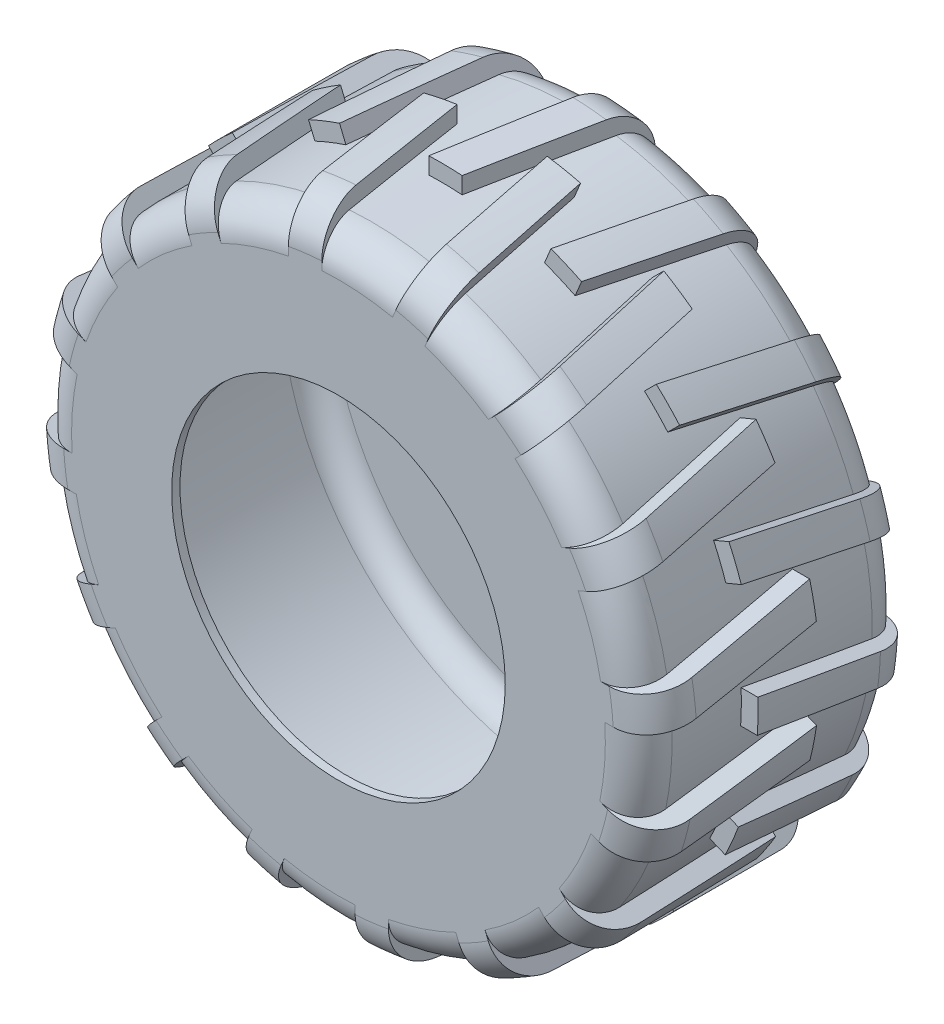
SolidWorks part; units mm, degrees
material "BUTYL"
ref_plane "Front Plane" through (0, 0, 0) normal (0, 0, 1) x (1, 0, 0)
ref_plane "Top Plane" through (0, 0, 0) normal (0, 1, 0) x (1, 0, 0)
ref_plane "Right Plane" through (0, 0, 0) normal (1, 0, 0) x (0, 0, -1)
sketch "Sketch1" plane through (0, 0, 0) normal (1, 0, 0) x (0, 0, -1)
  line L0 (0, 0) -> (-485.5709, 0) construction
  line L1 (-485.5709, 0) -> (498.8598, 0) construction
  line L2 (498.8598, 0) -> (0, 0) construction
  line L3 (0, 0) -> (0, -268.8161) construction
  line L4 (0, -268.8161) -> (0, 238.9616) construction
  line L5 (-203.2, 406.4) -> (-203.2, 254)
  line L6 (203.2, 406.4) -> (203.2, 254)
  line L7 (-152.4, 457.2) -> (152.4, 457.2)
  line L8 (0, 238.9616) -> (0, 521.9878) construction
  arc A0 (-152.4, 457.2) -> (-203.2, 406.4) centre (-152.4, 406.4) ccw
  arc A1 (203.2, 406.4) -> (152.4, 457.2) centre (152.4, 406.4) ccw
  point P8 (0, 457.2)
  point P11 (0, 457.2)
  point P13 (0, 0)
  dimension "D3" = 457.2
  dimension "D5" = 50.8
  dimension "D6" = 50.8
  dimension "D1" = 406.4
  dimension "D2" = 152.4
  dimension "D4" = 152.4
revolve "Revolve-Thin1" add sketch "Sketch1" angle 360 about L1 wall 12.7
ref_plane "Plane1" through (0, 482.6, 0) normal (0, 1, 0) x (1, 0, 0)
sketch "Sketch2" plane through (0, 482.6, 0) normal (0, 1, 0) x (1, 0, 0)
  line L0 (0, 0) -> (0, 264.3409) construction
  line L1 (0, 264.3409) -> (0, -257.8079) construction
  line L2 (0, -257.8079) -> (0, 0) construction
  line L3 (0, 0) -> (417.9852, 0) construction
  line L4 (417.9852, 0) -> (-428.4011, 0) construction
  line L5 (-18.7066, -46.9412) -> (32.0934, -46.9412)
  line L6 (25.4, 203.2) -> (76.2, 203.2)
  line L7 (254, 203.2) -> (-254, 203.2) construction
  line L8 (-18.7066, -46.9412) -> (25.4, 203.2)
  line L9 (32.0934, -46.9412) -> (76.2, 203.2)
  line L10 (-76.2, -203.2) -> (-25.4, -203.2)
  line L11 (-406.4, -203.2) -> (406.4, -203.2) construction
  line L12 (-25.4, -203.2) -> (-69.5066, 46.9412)
  line L13 (-69.5066, 46.9412) -> (-120.3066, 46.9412)
  line L14 (-120.3066, 46.9412) -> (-76.2, -203.2)
  point P12 (50.8, 203.2)
  point P17 (-50.8, -203.2)
  dimension "D1" = 50.8
  dimension "D2" = 50.8
  dimension "D3" = 10
  dimension "D4" = 50.8
  dimension "D5" = 254
  dimension "D6" = 50.8
  dimension "D7" = 50.8
  dimension "D8" = 50.8
  dimension "D9" = 254
  dimension "D10" = 10
extrude "Boss-Extrude1" add sketch "Sketch2" against normal up to next
pattern_circular "CirPattern1" count 16 over 360 about axis through (0, 0, 0) along (0, 0, 1) of "Boss-Extrude1"
sketch "Sketch3" plane through (0, 0, 0) normal (1, 0, 0) x (0, 0, -1)
  line L0 (0, 0) -> (-654.5394, 0) construction
  line L1 (-654.5394, 0) -> (728.2185, 0) construction
  line L2 (728.2185, 0) -> (0, 0) construction
  line L3 (0, 0) -> (0, 769.7248) construction
  line L4 (0, 769.7248) -> (0, -612.4088) construction
  line L5 (-139.7, 482.6) -> (139.7, 482.6)
  line L6 (-203.2, 419.1) -> (-203.2, 0)
  line L7 (-203.2, 25.4) -> (-203.2, -82.3647) construction
  line L8 (-203.2, 419.1) -> (-203.2, 647.7)
  line L9 (203.2, 419.1) -> (203.2, 0)
  line L10 (203.2, 419.1) -> (203.2, 0)
  line L11 (203.2, 419.1) -> (203.2, 647.7)
  line L12 (203.2, 268.8459) -> (203.2, 339.6451) construction
  line L13 (-203.2, 647.7) -> (203.2, 647.7)
  arc A0 (-139.7, 482.6) -> (-203.2, 419.1) centre (-139.7, 419.1) ccw
  arc A1 (203.2, 419.1) -> (139.7, 482.6) centre (139.7, 419.1) ccw
  point P8 (0, 0)
  point P15 (175.908, 419.1)
  point P16 (-230.3481, 419.1)
  point P18 (-230.3481, 419.1)
  point P20 (0, 0)
  point P21 (-230.3481, 419.1)
  point P22 (0, 0)
  point P25 (0, 0)
  dimension "D1" = 482.6
  dimension "D2" = 127
  dimension "D3" = 127
  dimension "D4" = 228.6
revolve "Cut-Revolve4" cut sketch "Sketch3" angle 360 about L1
